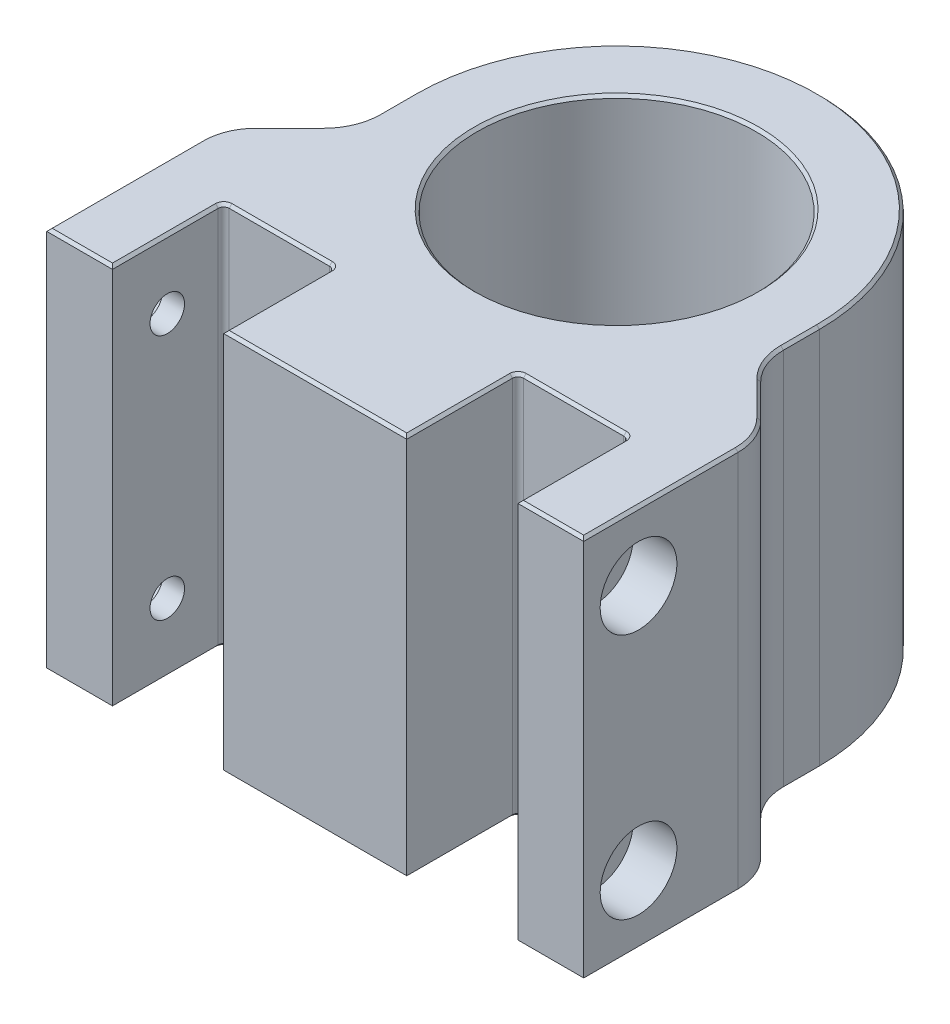
SolidWorks part; units mm, degrees
ref_plane "Front Plane" through (0, 0, 0) normal (0, 0, 1) x (1, 0, 0)
ref_plane "Top Plane" through (0, 0, 0) normal (0, 1, 0) x (1, 0, 0)
ref_plane "Right Plane" through (0, 0, 0) normal (1, 0, 0) x (0, 0, -1)
sketch "Sketch1" plane through (0, 0, 0) normal (0, 1, 0) x (1, 0, 0)
  line L0 (-37, 0) -> (-37, -55)
  line L1 (-37, -55) -> (37, -55)
  line L2 (37, -55) -> (37, 0)
  circle A0 centre (0, 0) radius 25.5
  arc A1 (37, 0) -> (-37, 0) centre (0, 0) ccw
  dimension "D1" = 51
  dimension "D2" = 37
  dimension "D3" = 55
extrude "Boss-Extrude1" add sketch "Sketch1" along normal mid plane 70
sketch "Sketch2" plane through (0, 35, 0) normal (0, 1, 0) x (1, 0, 0)
  line L1 (-37, -55) -> (-16.7, -55)
  line L2 (-37, -55) -> (-37, -34.7)
  line L3 (-37, -34.7) -> (-16.7, -34.7)
  line L4 (-16.7, -55) -> (-16.7, -34.7)
  line L5 (37, -55) -> (16.7, -55)
  line L6 (37, -55) -> (37, -34.7)
  line L7 (37, -34.7) -> (16.7, -34.7)
  line L8 (16.7, -55) -> (16.7, -34.7)
  dimension "D1" = 20.3
extrude "Cut-Extrude1" cut sketch "Sketch2" against normal through all
sketch "Sketch3" plane through (0, 35, 0) normal (0, 1, 0) x (1, 0, 0)
  line L0 (-37, -34.7) -> (-37, -55)
  line L2 (-37, -55) -> (-49, -55)
  line L3 (-49, -55) -> (-49, -22.7)
  line L4 (-49, -22.7) -> (-37, -10.7)
  line L5 (-37, 0) -> (-37, -34.7) construction
  line L6 (-37, -10.7) -> (-37, -34.7)
  line L7 (-16.7, -55) -> (16.7, -55) construction
  dimension "D1" = 12
  dimension "D2" = 135
  dimension "D3" = 12
extrude "Boss-Extrude2" add sketch "Sketch3" against normal up to surface (70 mm away) up to face at (0, -35, 26.475)
sketch "Sketch4" plane through (-49, 0, 0) normal (-1, 0, 0) x (0, 0, 1)
  line L0 (0, 0) -> (45, 0) construction
  line L1 (45, 0) -> (45, 22.5) construction
  line L2 (45, 0) -> (45, -22.5) construction
  line L3 (55, -35) -> (55, 35) construction
  circle A0 centre (45, 22.5) radius 3.15
  circle A1 centre (45, -22.5) radius 3.15
  dimension "D3" = 6.3
  dimension "D1" = 10
  dimension "D2" = 45
extrude "Cut-Extrude2" cut sketch "Sketch4" against normal blind 20
sketch "Sketch5" plane through (-49, 0, 0) normal (-1, 0, 0) x (0, 0, 1)
  circle A0 centre (45, 22.5) radius 7
  circle A1 centre (45, -22.5) radius 7
  dimension "D1" = 14
extrude "Cut-Extrude3" cut sketch "Sketch5" against normal blind 8
mirror "Mirror5" about plane through (0, 0, 0) normal (1, 0, 0) of "Cut-Extrude2", "Cut-Extrude3", "Boss-Extrude2"
fillet "Fillet1" radius 1 4 edges at (-16.7, 0, 34.7) (-37, 0, 34.7) (16.7, 0, 34.7) (37, 0, 34.7)
fillet "Fillet2" radius 10 4 edges at (-49, 0, 22.7) (-37, 0, 10.7) (49, 0, 22.7) (37, 0, 10.7)
chamfer "Chamfer1" distance 0.5 angle 45 50 edges at (0, -35, 25.5) (37.7612, -35, 10.3847) (37, -35, 3.2789) (0, -35, -37) (-37, -35, 3.2789) (-37.7612, -35, 10.3847) (-43, -35, 16.7) (-43, 35, 16.7) (-48.2388, -35, 23.0153) (-49, 35, 40.9211) (-49, -35, 40.9211) (-43, -35, 55) (-43, 35, 55) (-37, -35, 45.35) (-37, 35, 45.35) (-36.7071, -35, 34.9929) (-26.85, -35, 34.7) (-16.9929, -35, 34.9929) (-16.7, -35, 45.35) (0, -35, 55) (16.7, -35, 45.35) (16.9929, -35, 34.9929) (26.85, -35, 34.7) (36.7071, -35, 34.9929) (37, 35, 45.35) (37, -35, 45.35) (43, -35, 55) (43, 35, 55) (49, -35, 40.9211) (49, 35, 40.9211) (48.2388, -35, 23.0153) (43, 35, 16.7) (43, -35, 16.7) (0, 35, 25.5) (36.7071, 35, 34.9929) (26.85, 35, 34.7) (16.9929, 35, 34.9929) (16.7, 35, 45.35) (0, 35, 55) (-16.7, 35, 45.35) (-16.9929, 35, 34.9929) (-26.85, 35, 34.7) (-36.7071, 35, 34.9929) (-48.2388, 35, 23.0153) (-37.7612, 35, 10.3847) (-37, 35, 3.2789) (0, 35, -37) (37, 35, 3.2789) (37.7612, 35, 10.3847) (48.2388, 35, 23.0153)
